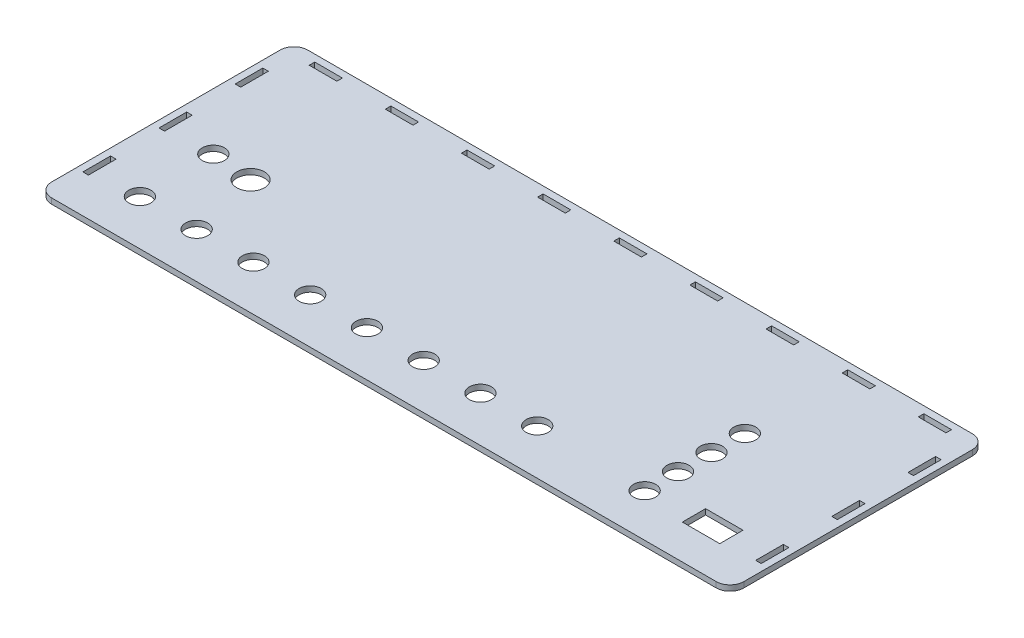
SolidWorks part; units mm, degrees
material "Acrylic (Medium-high impact)"
ref_plane "Front Plane" through (0, 0, 0) normal (0, 0, 1) x (1, 0, 0)
ref_plane "Top Plane" through (0, 0, 0) normal (0, 1, 0) x (1, 0, 0)
ref_plane "Right Plane" through (0, 0, 0) normal (1, 0, 0) x (0, 0, -1)
sketch "Sketch2" plane through (0, 0, 0) normal (0, 1, 0) x (1, 0, 0)
  line L1 (250, -92.5) -> (-250, -92.5)
  line L2 (250, -92.5) -> (250, 92.5)
  line L3 (250, 92.5) -> (-250, 92.5)
  line L4 (-250, -92.5) -> (-250, 92.5)
  line L5 (250, -92.5) -> (-250, 92.5) construction
  line L6 (250, 92.5) -> (-250, -92.5) construction
  point P0 (0, 0)
  dimension "D1" = 185
  dimension "D2" = 500
extrude "Base" add sketch "Sketch2" along normal blind 4
sketch "Sketch3" plane through (0, 4, 0) normal (0, 1, 0) x (1, 0, 0)
  line L10 (250, 92.5) -> (-250, 92.5) construction
  line L15 (-10, 83.5) -> (10, 83.5)
  line L16 (-10, 83.5) -> (-10, 87.5)
  line L17 (-10, 87.5) -> (10, 87.5)
  line L18 (10, 83.5) -> (10, 87.5)
  point P4 (0, 83.5)
  dimension "D1" = 20
  dimension "D2" = 4
  dimension "D3" = 5
extrude "Top Hole Definition" cut sketch "Sketch3" against normal through all
pattern_linear "Top Hole Pattern" count 5 spacing 55 along (-1, 0, 0) count 5 spacing 55 along (1, 0, 0) of "Top Hole Definition"
mirror "Bottom Hole" [suppressed] about plane through (0, 0, 0) normal (0, 0, 1)
sketch "Sketch4" plane through (0, 4, 0) normal (0, 1, 0) x (1, 0, 0)
  line L0 (-250, 92.5) -> (-250, -92.5) construction
  line L1 (-245, 10) -> (-241, 10)
  line L2 (-245, 10) -> (-245, -10)
  line L3 (-245, -10) -> (-241, -10)
  line L4 (-241, 10) -> (-241, -10)
  point P4 (-241, 0)
  dimension "D1" = 4
  dimension "D2" = 20
  dimension "D3" = 5
extrude "Left Hole Definition" cut sketch "Sketch4" against normal through all
pattern_linear "Left Hole Pattern" count 2 spacing 55 along (0, 0, -1) count 2 spacing 55 along (0, 0, 1) of "Left Hole Definition"
fillet "Fillet1" radius 10 4 edges at (250, 2, -92.5) (250, 2, 92.5) (-250, 2, -92.5) (-250, 2, 92.5)
mirror "Mirror2" about plane through (0, 0, 0) normal (1, 0, 0) of "Left Hole Pattern", "Left Hole Definition"
sketch "Sketch5" plane through (0, 4, 0) normal (0, 1, 0) x (1, 0, 0)
  line L0 (-240, -92.5) -> (240, -92.5) construction
  line L1 (241, -65) -> (241, -45) construction
  circle B0 centre (134.4438, -14.6561) radius 3.5
  circle B1 centre (82.0145, 6.5129) radius 1.2
  circle B2 centre (32.2746, 1.4193) radius 1.2
  circle B3 centre (7.4047, -1.1275) radius 1.2
  circle B4 centre (82.6665, 0.1462) radius 3.1
  circle B5 centre (117.8741, 48.987) radius 4
  circle B6 centre (14.984, -75.1405) radius 5
  circle B7 centre (39.854, -72.5936) radius 5
  circle B8 centre (64.7239, -70.0468) radius 5
  circle B9 centre (89.5938, -67.5) radius 5
  circle B10 centre (137.5, -44.5) radius 3.5
  circle B11 centre (117.6041, -46.5375) radius 4
  circle B12 centre (114.5479, -16.6935) radius 4
  circle B13 centre (87.047, -42.6301) radius 5
  circle B14 centre (62.1771, -45.1769) radius 5
  circle B15 centre (37.3071, -47.7237) radius 5
  circle B16 centre (12.4372, -50.2705) radius 5
  circle B17 centre (8.0567, -7.4942) radius 3.1
  circle B18 centre (32.9266, -4.9474) radius 3.1
  circle B19 centre (57.1446, 3.9661) radius 1.2
  circle B20 centre (57.7965, -2.4006) radius 3.1
  circle B21 centre (119.9116, 29.0911) radius 3.5
  circle B22 centre (25.4058, 19.4131) radius 3.5
  circle B23 centre (72.6587, 24.2521) radius 3.5
  circle B24 centre (70.6212, 44.1481) radius 4
  circle B25 centre (23.3683, 39.3091) radius 4
  dimension "D1" = 20
  dimension "D2" = 100
sketch_block_instance "IO-1"
sketch_block "IO"
extrude "Cut-Extrude3" [suppressed] cut sketch "Sketch5" against normal through all
sketch "Sketch6" [suppressed] plane through (0, 0, 0) normal (0, 1, 0) x (1, 0, 0)
  line L0 (36.5, 50.5) -> (36.5, 30.5) construction
  line L1 (36.5, 40.5) -> (71.5, 40.5) construction
  line L2 (131.5, 50.5) -> (131.5, 30.5) construction
  line L3 (84, 50.5) -> (84, 30.5) construction
  line L4 (84, 40.5) -> (119, 40.5) construction
  line L5 (131.5, 40.5) -> (166.5, 40.5) construction
  line L6 (41.5, 5.5) -> (66.5, 5.5) construction
  line L7 (54, 5.5) -> (54, -9.5) construction
  line L8 (4, -9.5) -> (104, -9.5) construction
  line L9 (41.5, -62.5) -> (66.5, -62.5) construction
  line L10 (54, -62.5) -> (54, -77.5) construction
  line L11 (4, -77.5) -> (104, -77.5) construction
  line L12 (121.5, -14.5) -> (141.5, -14.5) construction
  line L13 (131.5, -14.5) -> (131.5, -29.5) construction
  line L14 (106.5, -29.5) -> (156.5, -29.5) construction
  line L15 (121.5, -44.5) -> (141.5, -44.5) construction
  line L16 (131.5, -44.5) -> (131.5, -59.5) construction
  line L17 (106.5, -59.5) -> (156.5, -59.5) construction
  text T0 "PWM REFERENCE \r\nMODE" font "CATIA Symbols" height 2.5
  text T1 "PRESSURE\r\nREFERENCE MODE" font "CATIA Symbols" height 2.5
  text T2 "PATTERN\r\nREFERENCE MODE" font "CATIA Symbols" height 2.5
  text T3 "DISCRETE PRESSURE REFERENCE" font "CATIA Symbols" height 3.5
  text T4 "CONTINUOUS PRESSURE REFERENCE" font "CATIA Symbols" height 3.5
  text T5 "RUN" font "CATIA Symbols" height 3.5
  text T6 "INFINITY MODE" font "CATIA Symbols" height 3.5
  dimension "D1" = 35
  dimension "D2" = 100
  dimension "D3" = 15
  dimension "D4" = 15
  dimension "D5" = 100
  dimension "D6" = 15
  dimension "D7" = 50
  dimension "D8" = 15
  dimension "D9" = 50
extrude "Cut-Extrude4" [suppressed] cut sketch "Sketch6" along normal blind 0.1
sketch "Sketch7" plane through (0, 0, 0) normal (0, -1, 0) x (1, 0, 0)
  circle A0 centre (-209, 59.7983) radius 8
  circle A1 centre (-168, 59.7983) radius 8
  circle A2 centre (-127, 59.7983) radius 8
  circle A3 centre (-86, 59.7983) radius 8
  circle A4 centre (-45, 59.7983) radius 8
  circle A5 centre (-4, 59.7983) radius 8
  circle A6 centre (37, 59.7983) radius 8
  circle A7 centre (78, 59.7983) radius 8
  circle A8 centre (-179.5, 9.3102) radius 10
  circle A9 centre (-209, 6.7471) radius 8
  circle A10 centre (157.2983, 61.5) radius 8
  circle A11 centre (157.4318, 37.5004) radius 8
  circle A12 centre (157.5653, 13.5007) radius 8
  circle A13 centre (157.6987, -10.4989) radius 8
  dimension "D1" = 16
  dimension "D2" = 16
  dimension "D3" = 20
extrude "Cut-Extrude5" cut sketch "Sketch7" against normal through all
sketch "Sketch8" plane through (0, 0, 0) normal (0, -1, 0) x (1, 0, 0)
  line L0 (-240, 92.5) -> (240, 92.5) construction
  line L1 (190.5653, 67.5) -> (217.5653, 67.5)
  line L2 (190.5653, 67.5) -> (190.5653, 50.7)
  line L3 (190.5653, 50.7) -> (217.5653, 50.7)
  line L4 (217.5653, 67.5) -> (217.5653, 50.7)
  line L5 (190.5653, 67.5) -> (217.5653, 50.7) construction
  line L6 (190.5653, 50.7) -> (217.5653, 67.5) construction
  circle A1 centre (157.5653, 13.5007) radius 8 construction
  point P0 (204.0653, 59.1)
  dimension "D1" = 27
  dimension "D2" = 16.8
  dimension "D3" = 25
  dimension "D4" = 25
extrude "Cut-Extrude6" cut sketch "Sketch8" against normal through all
other "Freeze***"
